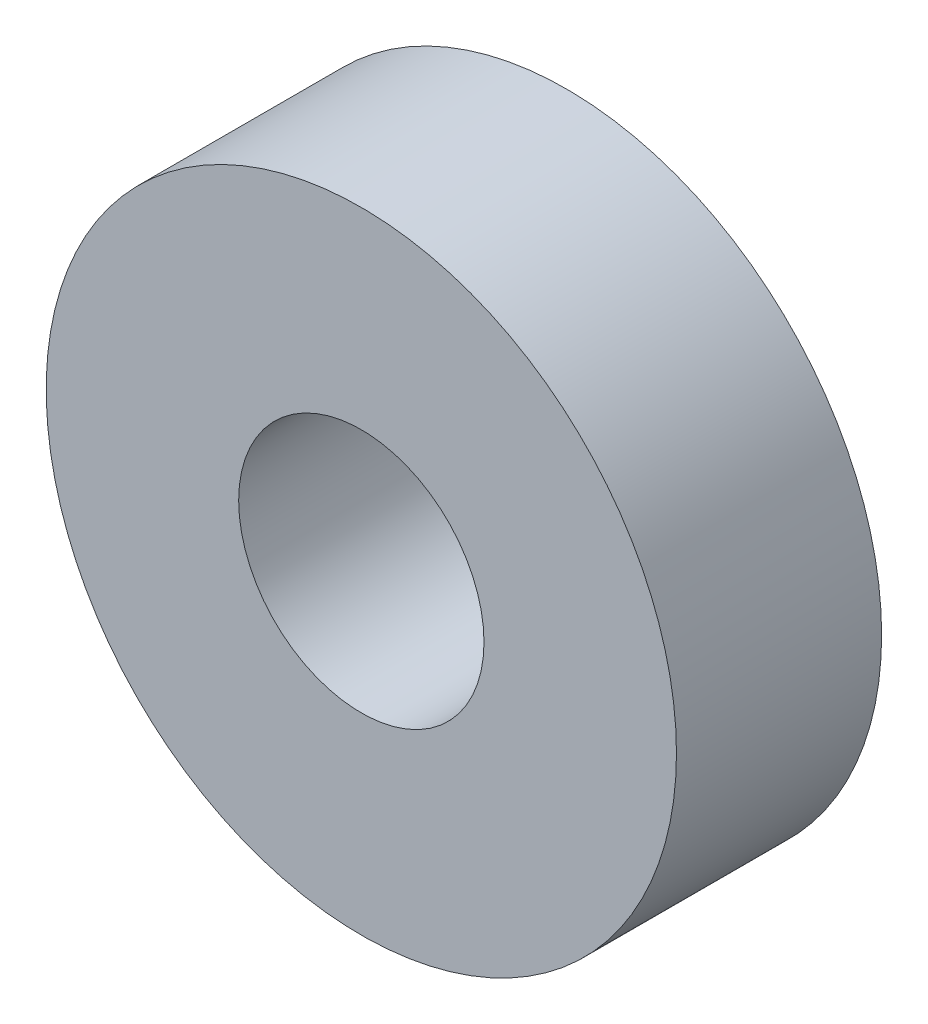
SolidWorks part; units mm, degrees
material "AISI 1020"
ref_plane "Plano frontal" through (0, 0, 0) normal (0, 0, 1) x (1, 0, 0)
ref_plane "Plano superior" through (0, 0, 0) normal (0, 1, 0) x (1, 0, 0)
ref_plane "Plano direito" through (0, 0, 0) normal (1, 0, 0) x (0, 0, -1)
sketch "Esboço1" plane through (0, 0, 0) normal (0, 0, 1) x (1, 0, 0)
  circle A0 centre (0, 0) radius 2.9
  circle A1 centre (0, 0) radius 7.45
  dimension "D1" = 14.9
  dimension "D2" = 5.8
extrude "Ressalto-extrusão1" add sketch "Esboço1" along normal blind 4.85
